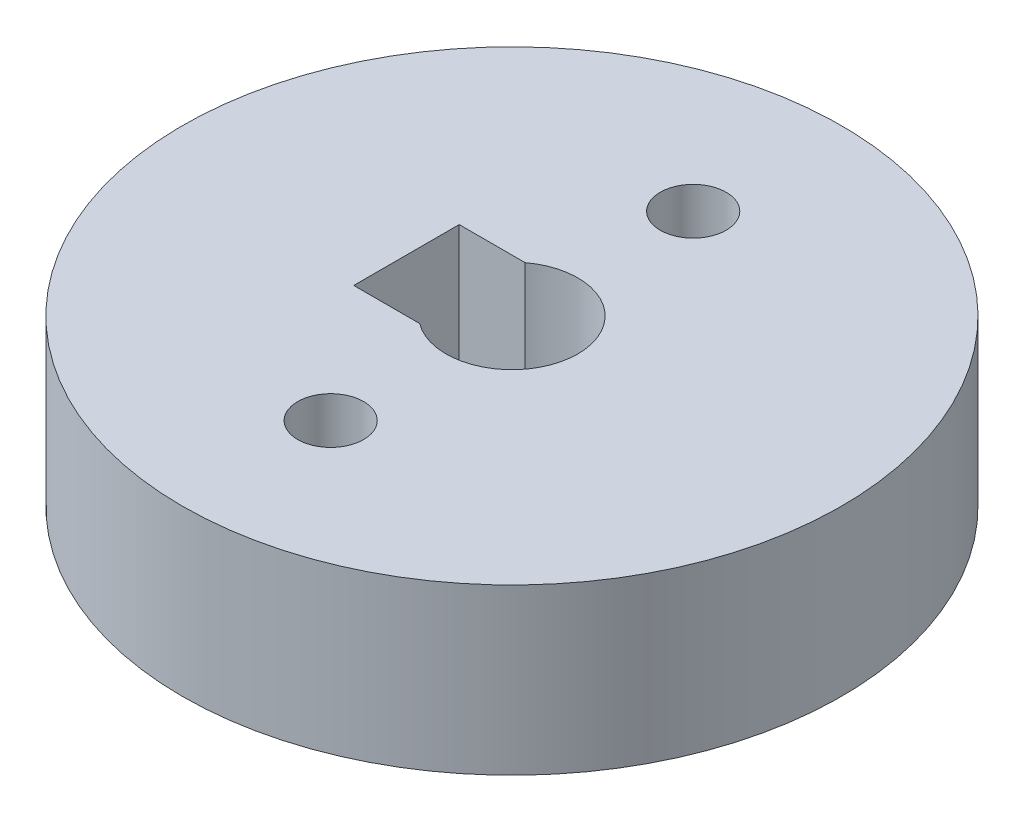
SolidWorks part; units mm, degrees
ref_plane "Front Plane" through (0, 0, 0) normal (0, 0, 1) x (1, 0, 0)
ref_plane "Top Plane" through (0, 0, 0) normal (0, 1, 0) x (1, 0, 0)
ref_plane "Right Plane" through (0, 0, 0) normal (1, 0, 0) x (0, 0, -1)
ref_plane "Plane1"
sketch "Sketch1" plane through (0, 0, 0) normal (0, 1, 0) x (-1, 0, 0)
  line L0 (1.2, 1.6) -> (3.2, 1.6)
  line L1 (3.2, 1.6) -> (3.2, -1.6)
  line L2 (3.2, -1.6) -> (1.2, -1.6)
  circle A0 centre (0, 0) radius 10
  arc A1 (1.2, 1.6) -> (1.2, -1.6) centre (0, 0) ccw
  dimension "D1" = 4
  dimension "D4" = 20
  dimension "D2" = 2
  dimension "D3" = 2
extrude "Extrusion1" add sketch "Sketch1" along normal blind 5 contours A0 A1 L0 L1 L2
hole_wizard "Hole1" positions "Sketch3" profile "Sketch2" legacy end condition through all
sketch "Sketch3" plane through (0, 5, 0) normal (0, 1, 0) x (1, 0, 0)
  point P1 (0, -5.5)
  point P2 (0, 5.5)
sketch "Sketch2" plane through (0, 5, 5.5) normal (1, 0, 0) x (0, 0, 1)
  line L0 (0, 0) -> (0, 5)
  line L1 (0, 5) -> (1, 5)
  line L2 (1, 5) -> (1, 0)
  line L3 (1, 0) -> (0, 0)
  line L4 (0, 110) -> (0, -10) construction
  dimension "Diameter" = 2
  dimension "Depth" = 5
